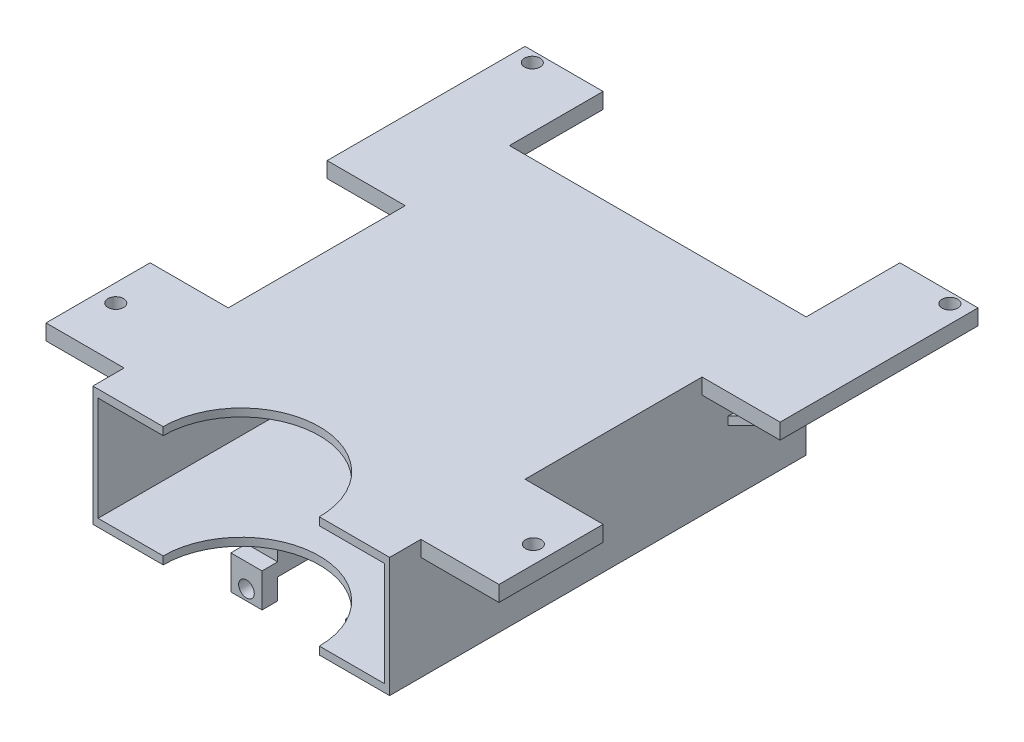
SolidWorks part; units mm, degrees
ref_plane "前视基准面" through (0, 0, 0) normal (0, 0, 1) x (1, 0, 0)
ref_plane "上视基准面" through (0, 0, 0) normal (0, 1, 0) x (1, 0, 0)
ref_plane "右视基准面" through (0, 0, 0) normal (1, 0, 0) x (0, 0, -1)
other "Configuration Table"
sketch "草图1" plane through (0, 0, 0) normal (0, 0, 1) x (1, 0, 0)
  line L1 (0, 0) -> (57, 0)
  line L2 (0, 0) -> (0, 23)
  line L3 (0, 23) -> (57, 23)
  line L4 (57, 0) -> (57, 23)
  dimension "D1" = 57
  dimension "D2" = 23
extrude "凸台-拉伸1" add sketch "草图1" along normal blind 80
sketch "草图2" plane through (0, 0, 80) normal (0, 0, 1) x (1, 0, 0)
  line L0 (0, 23) -> (0, 0) construction
  line L1 (1, 21.5) -> (56, 21.5)
  line L2 (1, 21.5) -> (1, 1.5)
  line L3 (1, 1.5) -> (56, 1.5)
  line L4 (56, 21.5) -> (56, 1.5)
  line L5 (57, 23) -> (0, 23) construction
  dimension "D1" = 55
  dimension "D2" = 20
  dimension "D3" = 1
  dimension "D4" = 1.5
extrude "切除-拉伸1" cut sketch "草图2" against normal blind 75
sketch "草图3" plane through (0, 0, 0) normal (0, -1, 0) x (1, 0, 0)
  line L0 (28.5, 80) -> (28.5, 0) construction
  line L1 (0, 80) -> (57, 80) construction
  line L2 (0, 0) -> (57, 0) construction
  line L4 (14.5, 65) -> (20.5, 65)
  line L5 (14.5, 65) -> (14.5, 59)
  line L6 (14.5, 59) -> (20.5, 59)
  line L7 (20.5, 65) -> (20.5, 59)
  line L8 (14.5, 10) -> (20.5, 10)
  line L9 (14.5, 10) -> (14.5, 4)
  line L10 (14.5, 4) -> (20.5, 4)
  line L11 (20.5, 10) -> (20.5, 4)
  line L12 (42.5, 10) -> (42.5, 4)
  line L13 (42.5, 4) -> (36.5, 4)
  line L14 (36.5, 10) -> (36.5, 4)
  line L15 (42.5, 10) -> (36.5, 10)
  line L16 (42.5, 59) -> (36.5, 59)
  line L17 (36.5, 65) -> (36.5, 59)
  line L18 (42.5, 65) -> (36.5, 65)
  line L19 (42.5, 65) -> (42.5, 59)
  dimension "D1" = 6
  dimension "D2" = 49
  dimension "D3" = 14
  dimension "D4" = 15
extrude "凸台-拉伸2" add sketch "草图3" along normal blind 6
ref_plane "基准面1" through (28.5, 0, 0) normal (-1, 0, 0) x (0, 0, 1)
ref_plane "基准面2" through (0, 0, 34.5) normal (0, 0, 1) x (1, 0, 0)
sketch "草图4" plane through (0, 0, 65) normal (0, 0, 1) x (1, 0, 0)
  line L0 (36.5, -6) -> (36.5, 0) construction
  line L1 (36.5, -3.5) -> (42.5, -3.5)
  line L2 (36.5, -3.5) -> (36.5, -10)
  line L3 (36.5, -10) -> (42.5, -10)
  line L4 (42.5, -3.5) -> (42.5, -10)
  line L5 (42.5, -6) -> (36.5, -6) construction
  line L6 (39.5, -3.5) -> (39.5, -10) construction
  circle A0 centre (39.5, -8) radius 1.5
  dimension "D4" = 3
  dimension "D1" = 6
  dimension "D2" = 2.5
  dimension "D3" = 4
  dimension "D5" = 2
extrude "凸台-拉伸3" add sketch "草图4" along normal blind 3
mirror "镜向1" about plane through (0, 0, 34.5) normal (0, 0, 1) of "凸台-拉伸3"
mirror "镜向2" about plane through (28.5, 0, 0) normal (-1, 0, 0) of "镜向1", "凸台-拉伸3"
sketch "草图5" plane through (0, 23, 0) normal (0, 1, 0) x (1, 0, 0)
  line L0 (57, -80) -> (0, -80) construction
  line L1 (13.5, -80) -> (43.5, -80) construction
  arc A0 (43.5, -80) -> (13.5, -80) centre (28.5, -80) ccw
  dimension "D1" = 30
extrude "切除-拉伸3" cut sketch "草图5" against normal blind 25 and the other way through all
sketch "草图6" plane through (0, 0, 0) normal (-1, 0, 0) x (0, 0, 1)
  line L0 (80, 23) -> (0, 23) construction
  line L1 (20, 23) -> (-18, 23)
  line L2 (20, 23) -> (20, 20)
  line L3 (20, 20) -> (-18, 20)
  line L4 (-18, 23) -> (-18, 20)
  line L5 (0, 23) -> (0, 0) construction
  line L7 (54, 23) -> (74, 23)
  line L8 (54, 23) -> (54, 20)
  line L9 (54, 20) -> (74, 20)
  line L10 (74, 23) -> (74, 20)
  point P12 (-18, 21.5)
  dimension "D1" = 3
  dimension "D2" = 20
  dimension "D3" = 18
  dimension "D4" = 3
  dimension "D5" = 20
  dimension "D6" = 72
extrude "凸台-拉伸4" add sketch "草图6" along normal blind 15
mirror "镜向3" about plane through (28.5, 0, 0) normal (-1, 0, 0) of "凸台-拉伸4"
sketch "草图8" plane through (0, 23, 0) normal (0, 1, 0) x (1, 0, 0)
  line L0 (-15, 18) -> (0, 18) construction
  line L4 (-15, -20) -> (-15, 18) construction
  line L5 (28.5, 12.65) -> (28.5, -12.65) construction
  circle A0 centre (-11.6, 16) radius 1.5
  circle A1 centre (68.6, 16) radius 1.5
  circle A2 centre (-11.6, -64) radius 1.5
  circle A3 centre (68.6, -64) radius 1.5
  point P14 (0, 0)
  point P15 (0, 0)
  point P16 (0, 0)
  dimension "D3" = 3
  dimension "D1" = 2
  dimension "D2" = 3.4
  dimension "D4" = 80
extrude "切除-拉伸4" cut sketch "草图8" against normal through all
ref_plane "基准面3" through (0, 0, 10) normal (0, 0, -1) x (-1, 0, 0)
sketch "草图12" plane through (0, 0, 10) normal (0, 0, -1) x (-1, 0, 0)
  line L0 (15, 20) -> (0, 12.4)
  line L1 (0, 20) -> (0, 0) construction
  line L2 (11.8421, 20) -> (0, 14)
  line L3 (15, 20) -> (0, 20) construction
  line L4 (11.8421, 20) -> (15, 20)
  line L5 (0, 14) -> (0, 12.4)
  dimension "D1" = 7.6
  dimension "D2" = 6
extrude "凸台-拉伸5" add sketch "草图12" against normal blind 5 and the other way blind 5
mirror "镜向4" about plane through (28.5, 0, 0) normal (-1, 0, 0) of "凸台-拉伸5"
